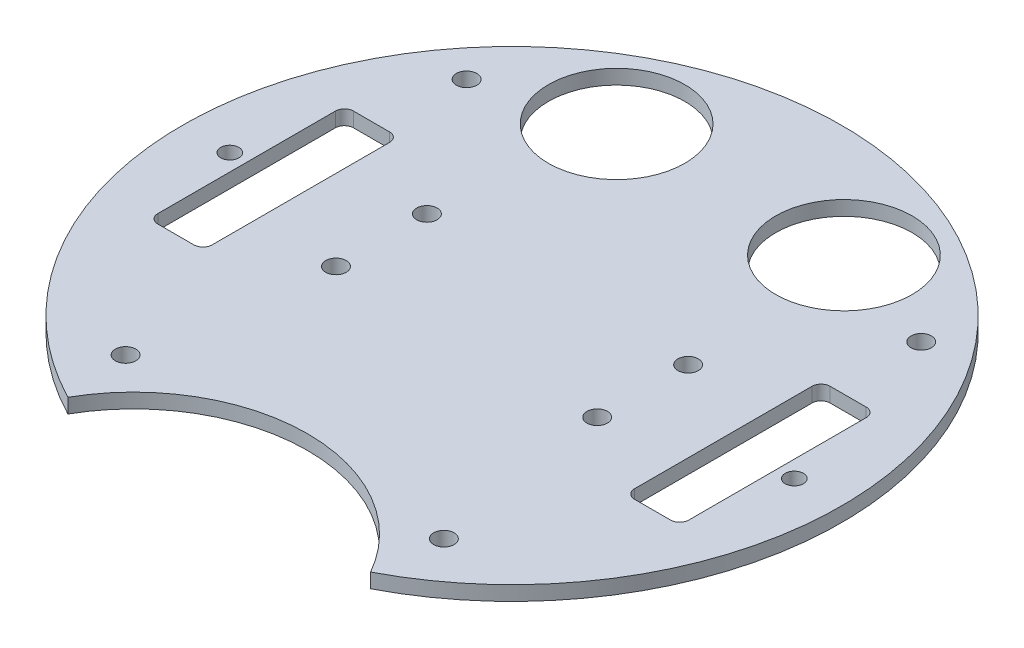
SolidWorks part; units mm, degrees
material "Plain Carbon Steel"
ref_plane "Front Plane" through (0, 0, 0) normal (0, 0, 1) x (1, 0, 0)
ref_plane "Top Plane" through (0, 0, 0) normal (0, 1, 0) x (1, 0, 0)
ref_plane "Right Plane" through (0, 0, 0) normal (1, 0, 0) x (0, 0, -1)
sketch "Sketch1" plane through (0, 0, 0) normal (0, 1, 0) x (1, 0, 0)
  line L0 (0, -83.2398) -> (-33.2911, -64.4046) construction
  line L1 (0, -83.2398) -> (0, 0) construction
  arc A0 (33.2911, -64.4046) -> (-33.2911, -64.4046) centre (0, 0) ccw
  arc A1 (33.2911, -64.4046) -> (-33.2911, -64.4046) centre (0, -83.2398) ccw
  dimension "D1" = 145
  dimension "D2" = 76.5
  dimension "D3" = 60.5
extrude "Boss-Extrude1" add sketch "Sketch1" along normal blind 3.2
sketch "solenoid placement" plane through (0, 3.2, 0) normal (0, 1, 0) x (1, 0, 0)
  line L0 (0, 0) -> (0, -36) construction
  line L1 (0, -36) -> (0, -44.9898) construction
  line L2 (-19, -36) -> (19, -36)
  line L3 (-19, -36) -> (-19, 28.4)
  line L4 (-19, 28.4) -> (19, 28.4)
  line L5 (19, -36) -> (19, 28.4)
  circle A1 centre (0, 0) radius 72.5 construction
  arc A2 (33.2911, -64.4046) -> (-33.2911, -64.4046) centre (0, 0) ccw construction
  arc A3 (33.2911, -64.4046) -> (-33.2911, -64.4046) centre (0, -83.2398) ccw construction
  dimension "D1" = 64.4
  dimension "D2" = 36
  dimension "D4" = 38
sketch "Sketch2" plane through (0, 3.2, 0) normal (0, 1, 0) x (1, 0, 0)
  line L1 (-57.5, 20.6344) -> (-47.34, 20.6344) construction
  line L2 (-57.5, 20.6344) -> (-57.5, -20.6344) construction
  line L3 (-57.5, -20.6344) -> (-47.34, -20.6344) construction
  line L4 (-47.34, 20.6344) -> (-47.34, -20.6344) construction
  line L8 (-57.8, -20.9344) -> (-47.04, -20.9344)
  line L9 (-47.04, 20.9344) -> (-47.04, -20.9344)
  line L10 (-57.8, 20.9344) -> (-47.04, 20.9344)
  line L11 (-57.8, 20.9344) -> (-57.8, -20.9344)
  line L12 (0, 0) -> (0, 72.5) construction
  line L13 (47.34, 20.6344) -> (47.34, -20.6344) construction
  line L14 (57.5, -20.6344) -> (47.34, -20.6344) construction
  line L15 (57.5, 20.6344) -> (57.5, -20.6344) construction
  line L16 (57.5, 20.6344) -> (47.34, 20.6344) construction
  line L17 (57.8, 20.9344) -> (57.8, -20.9344)
  line L18 (57.8, 20.9344) -> (47.04, 20.9344)
  line L19 (47.04, 20.9344) -> (47.04, -20.9344)
  line L20 (57.8, -20.9344) -> (47.04, -20.9344)
  arc A0 (33.2911, -64.4046) -> (-33.2911, -64.4046) centre (0, 0) ccw construction
  dimension "D1" = 0.3
extrude "Cut-Extrude1" cut sketch "Sketch2" against normal through all
sketch "Sketch3" plane through (0, 0, 0) normal (0, -1, 0) x (1, 0, 0)
  line L0 (0, 0) -> (0, -72.5) construction
  circle A0 centre (-62.08, 0) radius 2
  circle A1 centre (-28.73, 10) radius 2.25
  circle A2 centre (-28.73, -10) radius 2.25
  arc A3 (-33.2911, 64.4046) -> (33.2911, 64.4046) centre (0, 0) ccw construction
  circle A4 centre (28.73, -10) radius 2.25
  circle A5 centre (28.73, 10) radius 2.25
  circle A6 centre (62.08, 0) radius 2
  dimension "D1" = 4
  dimension "D2" = 4.5
extrude "Cut-Extrude2" cut sketch "Sketch3" against normal through all
sketch "Sketch4" plane through (0, 3.2, 0) normal (0, 1, 0) x (1, 0, 0)
  line L0 (0, 0) -> (0, 72.5) construction
  line L1 (0, 48) -> (-25, 48) construction
  circle A0 centre (-25, 48) radius 15
  arc A1 (33.2911, -64.4046) -> (-33.2911, -64.4046) centre (0, 0) ccw construction
  circle A2 centre (25, 48) radius 15
  dimension "D1" = 30
  dimension "D2" = 48
  dimension "D3" = 25
extrude "Cut-Extrude3" cut sketch "Sketch4" against normal through all
sketch "Sketch5" plane through (0, 3.2, 0) normal (0, 1, 0) x (1, 0, 0)
  line L0 (0, 0) -> (0, 72.5) construction
  line L1 (-56.3858, 21.5201) -> (-48.4542, 21.5201)
  line L2 (-58.3858, 19.5201) -> (-58.3858, -19.5201)
  line L3 (-56.3858, -21.5201) -> (-48.4542, -21.5201)
  line L4 (-46.4542, 19.5201) -> (-46.4542, -19.5201)
  line L5 (46.4542, 19.5201) -> (46.4542, -19.5201)
  line L6 (56.3858, -21.5201) -> (48.4542, -21.5201)
  line L7 (58.3858, 19.5201) -> (58.3858, -19.5201)
  line L8 (56.3858, 21.5201) -> (48.4542, 21.5201)
  arc A0 (-58.3858, -19.5201) -> (-56.3858, -21.5201) centre (-56.3858, -19.5201) ccw
  arc A1 (-48.4542, -21.5201) -> (-46.4542, -19.5201) centre (-48.4542, -19.5201) ccw
  arc A2 (-48.4542, 21.5201) -> (-46.4542, 19.5201) centre (-48.4542, 19.5201) cw
  arc A3 (-56.3858, 21.5201) -> (-58.3858, 19.5201) centre (-56.3858, 19.5201) ccw
  arc A4 (33.2911, -64.4046) -> (-33.2911, -64.4046) centre (0, 0) ccw construction
  arc A5 (56.3858, 21.5201) -> (58.3858, 19.5201) centre (56.3858, 19.5201) cw
  arc A6 (48.4542, 21.5201) -> (46.4542, 19.5201) centre (48.4542, 19.5201) ccw
  arc A7 (48.4542, -21.5201) -> (46.4542, -19.5201) centre (48.4542, -19.5201) cw
  arc A8 (58.3858, -19.5201) -> (56.3858, -21.5201) centre (56.3858, -19.5201) cw
  point P15 (-57.8, 20.9344)
  dimension "D1" = 2
extrude "Cut-Extrude4" cut sketch "Sketch5" against normal through all
sketch "Sketch6" plane through (0, 3.2, 0) normal (0, 1, 0) x (1, 0, 0)
  line L0 (0, 72.5) -> (0, -44.9898) construction
  circle A0 centre (-50, 40) radius 2.25
  circle A1 centre (-35, -50) radius 2.25
  arc A4 (33.2911, -64.4046) -> (-33.2911, -64.4046) centre (0, 0) ccw construction
  arc A5 (33.2911, -64.4046) -> (-33.2911, -64.4046) centre (0, -83.2398) ccw construction
  circle A6 centre (35, -50) radius 2.25
  circle A7 centre (50, 40) radius 2.25
  dimension "D3" = 4.5
  dimension "D1" = 35
  dimension "D2" = 50
  dimension "D4" = 50
  dimension "D5" = 40
extrude "Cut-Extrude5" cut sketch "Sketch6" against normal through all
chamfer "Chamfer1" [suppressed] distance 2 angle 41
equation "\"smallPulleyTeeth\"= 15"
equation "\"largePulleyTeeth\"= 30"
equation "\"eighthThick\"= 2.9mm"
equation "\"sixteenthThick\"= 1.7mm"
equation "\"quarterThick\"=5.9mm"
equation "\"OD\"= 145mm"
equation "\"puckAngle\"= 60.5deg"
equation "\"D1@Sketch1\"=\"OD\""
equation "\"puckDiam\"= 76.5mm"
equation "\"D2@Sketch1\"=\"puckDiam\""
equation "\"D3@Sketch1\"=\"puckAngle\""
equation "\"D1@Boss-Extrude1\"=\"eighthThick\""
equation "\"axlePress\"= 5.9mm"
equation "\"press\"= 0.2mm"
equation "\"wheelClear\"= 0.3mm"
equation "\"D1@Sketch2\"=\"wheelClear\""
equation "\"10-32clear\"= 4.5mm"
equation "\"6-32clear\"= 3.3mm"
equation "\"8-32clear\"= 4.0mm"
equation "\"wheelHeight\"= 22mm"
equation "\"D1@Sketch3\"=\"8-32clear\""
equation "\"D2@Sketch3\"=\"10-32clear\""
equation "\"D3@Sketch6\"=\"10-32clear\""
